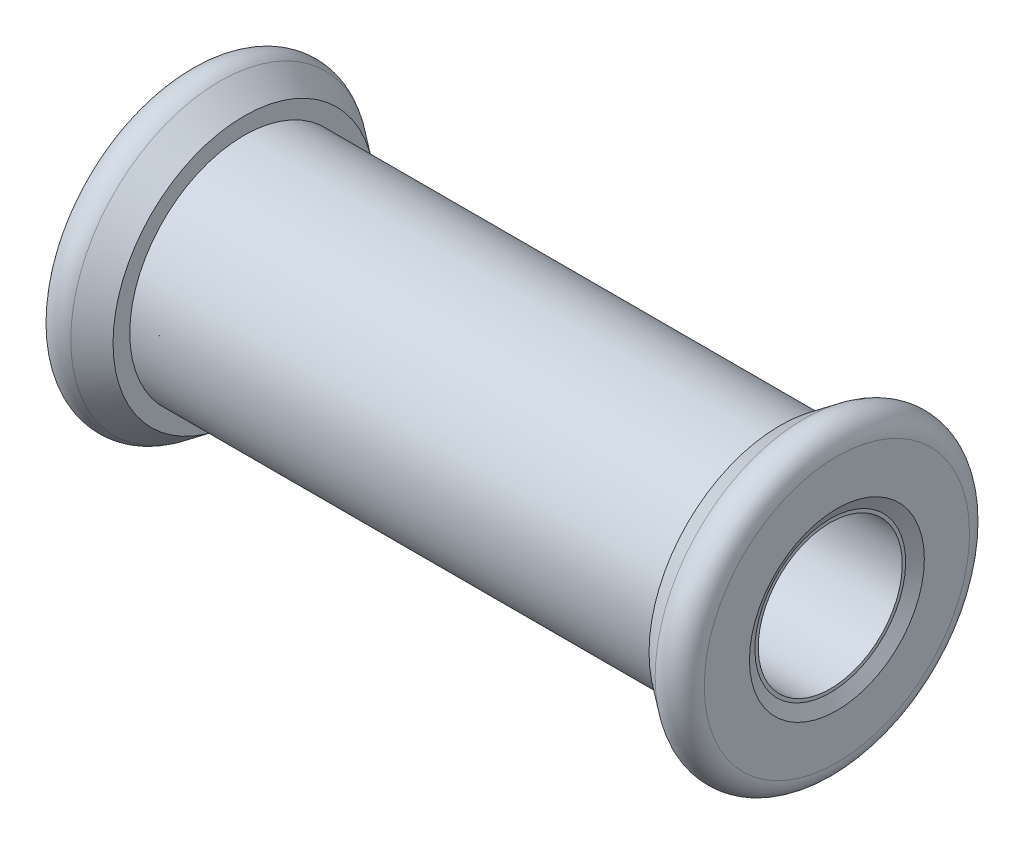
SolidWorks part; units mm, degrees
ref_plane "Front Plane" through (0, 0, 0) normal (0, 0, 1) x (1, 0, 0)
ref_plane "Top Plane" through (0, 0, 0) normal (0, 1, 0) x (1, 0, 0)
ref_plane "Right Plane" through (0, 0, 0) normal (1, 0, 0) x (0, 0, -1)
sketch "Sketch1" plane through (0, 0, 0) normal (0, 0, 1) x (1, 0, 0)
  line L0 (-9.2505, 0) -> (-45.8395, 0) construction
  line L1 (-37.045, 0) -> (-18.045, 0)
  line L2 (-35.545, 3.41) -> (-19.545, 3.41)
  line L3 (-19.545, 3.41) -> (-19.545, 3.91)
  line L4 (-19.545, 3.91) -> (-18.823, 4.4491)
  line L5 (-17.8466, 3.9596) -> (-17.8466, 2.6104)
  line L6 (-17.8466, 2.6104) -> (-18.045, 2.25)
  line L7 (-18.045, 2.25) -> (-18.045, 0)
  line L8 (-27.545, 0) -> (-27.545, 18.3792) construction
  line L9 (-37.2435, 2.6104) -> (-37.045, 2.25)
  line L10 (-37.2435, 3.9596) -> (-37.2435, 2.6104)
  line L11 (-35.545, 3.91) -> (-36.267, 4.4491)
  line L12 (-35.545, 3.41) -> (-35.545, 3.91)
  line L13 (-37.045, 2.25) -> (-37.045, 0)
  arc A0 (-18.823, 4.4491) -> (-17.8466, 3.9596) centre (-18.4575, 3.9596) cw
  arc A1 (-36.267, 4.4491) -> (-37.2435, 3.9596) centre (-36.6325, 3.9596) ccw
  point P5 (-27.545, 0)
  point P6 (-27.545, 0)
  point P12 (-18.823, 4.4491)
  dimension "D1" = 19
  dimension "D2" = 1.5
  dimension "D3" = 3.41
  dimension "D4" = 0.5
  dimension "D5" = 2.25
revolve "Revolve1" add sketch "Sketch1" angle 360 about L0
sketch "Sketch4" plane through (-18.045, 0, 0) normal (1, 0, 0) x (0, 0, -1)
  circle A0 centre (0, 0) radius 2.15
  dimension "D1" = 4.3
extrude "Cut-Extrude1" cut sketch "Sketch4" against normal blind 28
